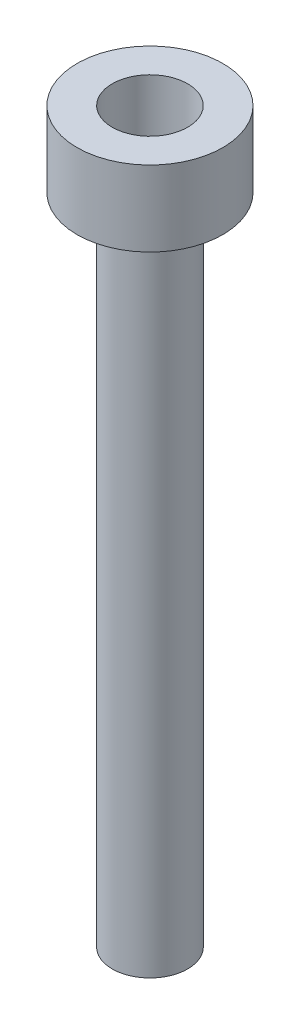
SolidWorks part; units mm, degrees
ref_plane "前视基准面" through (0, 0, 0) normal (0, 0, 1) x (1, 0, 0)
ref_plane "上视基准面" through (0, 0, 0) normal (0, 1, 0) x (1, 0, 0)
ref_plane "右视基准面" through (0, 0, 0) normal (1, 0, 0) x (0, 0, -1)
sketch "草图1" plane through (0, 0, 0) normal (0, 1, 0) x (1, 0, 0)
  circle A0 centre (0, 0) radius 2.9
  dimension "D1" = 5.8
extrude "凸台-拉伸1" add sketch "草图1" along normal blind 3
sketch "草图2" plane through (0, 3, 0) normal (0, 1, 0) x (1, 0, 0)
  circle A0 centre (0, 0) radius 1.5
  dimension "D1" = 3
extrude "切除-拉伸1" cut sketch "草图2" against normal blind 3
sketch "草图5" plane through (0, 0, 0) normal (0, -1, 0) x (1, 0, 0)
  circle A0 centre (0, 0) radius 1.5
extrude "凸台-拉伸2" add sketch "草图5" along normal blind 26 separate body
